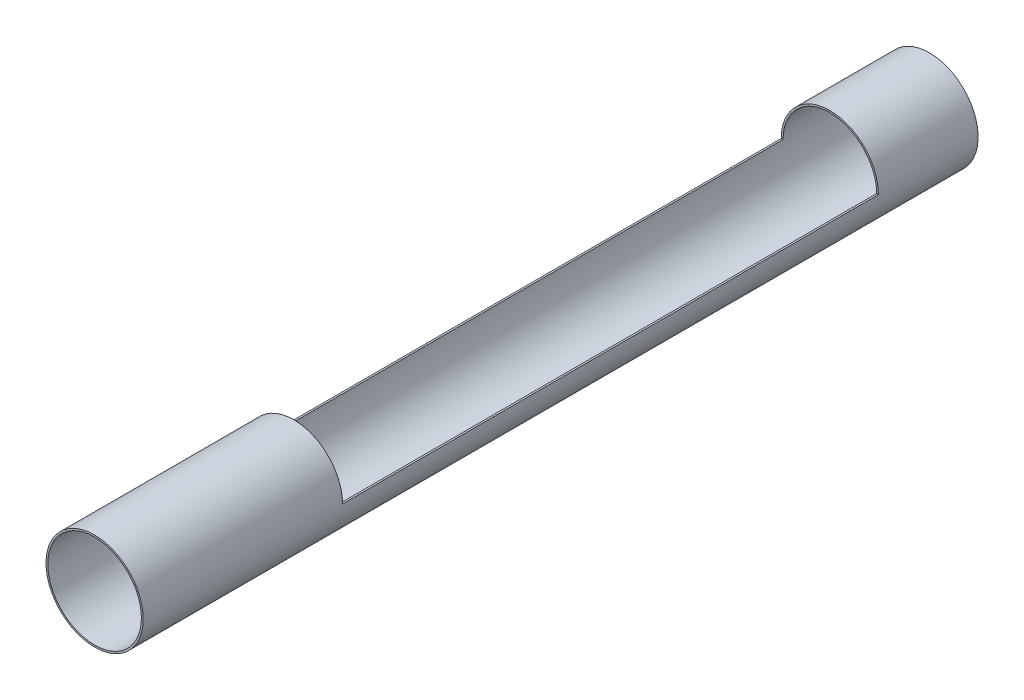
SolidWorks part; units mm, degrees
ref_plane "Front Plane" through (0, 0, 0) normal (0, 0, 1) x (1, 0, 0)
ref_plane "Top Plane" through (0, 0, 0) normal (0, 1, 0) x (1, 0, 0)
ref_plane "Right Plane" through (0, 0, 0) normal (1, 0, 0) x (0, 0, -1)
sketch "Sketch1" plane through (0, 0, 0) normal (0, 0, 1) x (1, 0, 0)
  line L0 (-49.5046, 0) -> (-47.6885, 0)
  line L1 (47.6885, 0) -> (49.5046, 0)
  arc A0 (-49.5046, 0) -> (49.5046, 0) centre (0, 0) ccw
  arc A1 (-47.6885, 0) -> (47.6885, 0) centre (0, 0) ccw
  dimension "D1" = 95.377
  dimension "D2" = 99.0092
extrude "Boss-Extrude1" add sketch "Sketch1" along normal blind 546.1
sketch "Sketch2" plane through (0, 0, 546.1) normal (0, 0, 1) x (1, 0, 0)
  circle A0 centre (0, 0) radius 47.6885
  circle A1 centre (0, 0) radius 49.5046
  arc A2 (-47.6885, 0) -> (47.6885, 0) centre (0, 0) ccw construction
  arc A3 (-49.5046, 0) -> (49.5046, 0) centre (0, 0) ccw construction
extrude "Boss-Extrude2" add sketch "Sketch2" along normal blind 203.2
sketch "Sketch3" plane through (0, 0, 0) normal (0, 0, -1) x (-1, 0, 0)
  circle A0 centre (0, 0) radius 47.6885
  circle A1 centre (0, 0) radius 49.5046
  arc A2 (-47.6885, 0) -> (47.6885, 0) centre (0, 0) ccw construction
  arc A3 (-49.5046, 0) -> (49.5046, 0) centre (0, 0) ccw construction
extrude "Boss-Extrude3" add sketch "Sketch3" along normal blind 101.6
